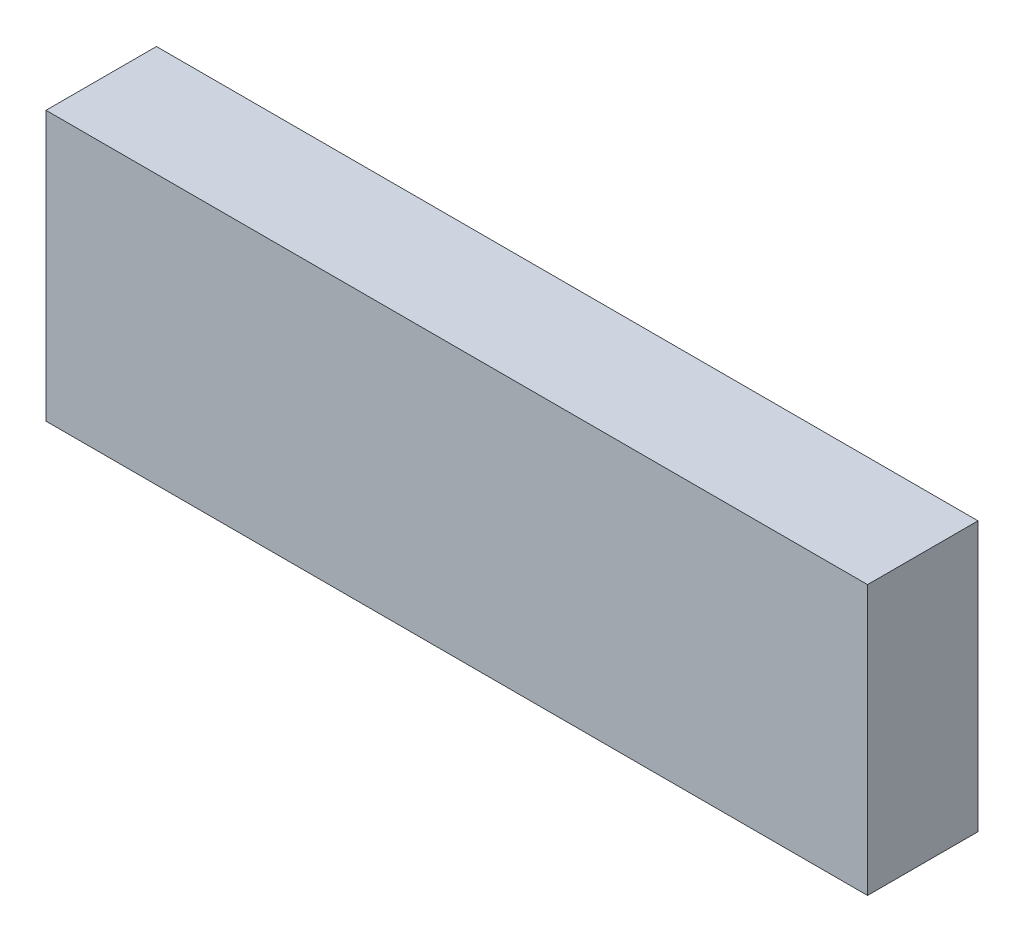
SolidWorks part; units mm, degrees
ref_plane "Спереди" through (0, 0, 0) normal (0, 0, 1) x (1, 0, 0)
ref_plane "Сверху" through (0, 0, 0) normal (0, 1, 0) x (1, 0, 0)
ref_plane "Справа" through (0, 0, 0) normal (1, 0, 0) x (0, 0, -1)
sketch "Эскиз1" plane through (0, 0, 0) normal (0, 0, 1) x (1, 0, 0)
  line L1 (-11.9, -3.9) -> (11.9, -3.9)
  line L2 (-11.9, -3.9) -> (-11.9, 3.9)
  line L3 (-11.9, 3.9) -> (11.9, 3.9)
  line L4 (11.9, -3.9) -> (11.9, 3.9)
  line L5 (-11.9, -3.9) -> (11.9, 3.9) construction
  line L6 (-11.9, 3.9) -> (11.9, -3.9) construction
  point P0 (0, 0)
  dimension "D1" = 23.8
  dimension "D2" = 7.8
extrude "Бобышка-Вытянуть1" add sketch "Эскиз1" along normal blind 3.2
sketch "Эскиз2" plane through (0, 0, 0) normal (0, 0, -1) x (-1, 0, 0)
  circle A0 centre (0, 0) radius 2.5
  circle A1 centre (8, 0) radius 2.5
  circle A2 centre (-8, 0) radius 2.5
  dimension "D1" = 8
  dimension "D2" = 8
extrude "Вырез-Вытянуть1" cut sketch "Эскиз2" against normal blind 1.8
